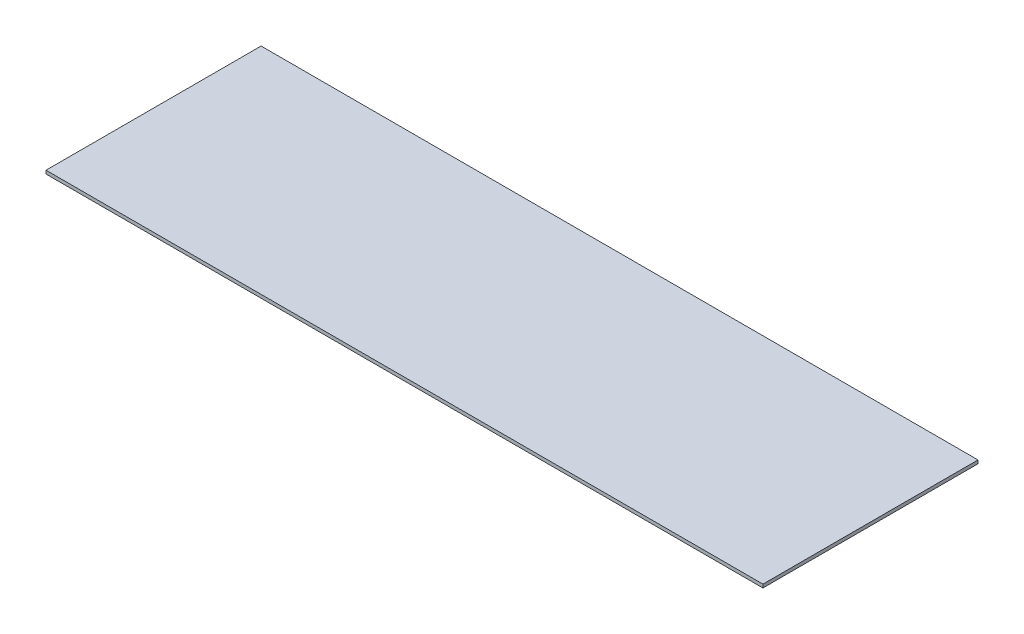
SolidWorks part; units mm, degrees
material "3003 Alloy"
ref_plane "Front Plane" through (0, 0, 0) normal (0, 0, 1) x (1, 0, 0)
ref_plane "Top Plane" through (0, 0, 0) normal (0, 1, 0) x (1, 0, 0)
ref_plane "Right Plane" through (0, 0, 0) normal (1, 0, 0) x (0, 0, -1)
sketch "Sketch1" plane through (0, 0, 0) normal (0, 1, 0) x (1, 0, 0)
  line L1 (0, 0) -> (1016, 0)
  line L2 (0, 0) -> (0, 304.8)
  line L3 (0, 304.8) -> (1016, 304.8)
  line L4 (1016, 0) -> (1016, 304.8)
  dimension "D1" = 304.8
  dimension "D2" = 1016
extrude "Boss-Extrude1" add sketch "Sketch1" along normal blind 4.7625
